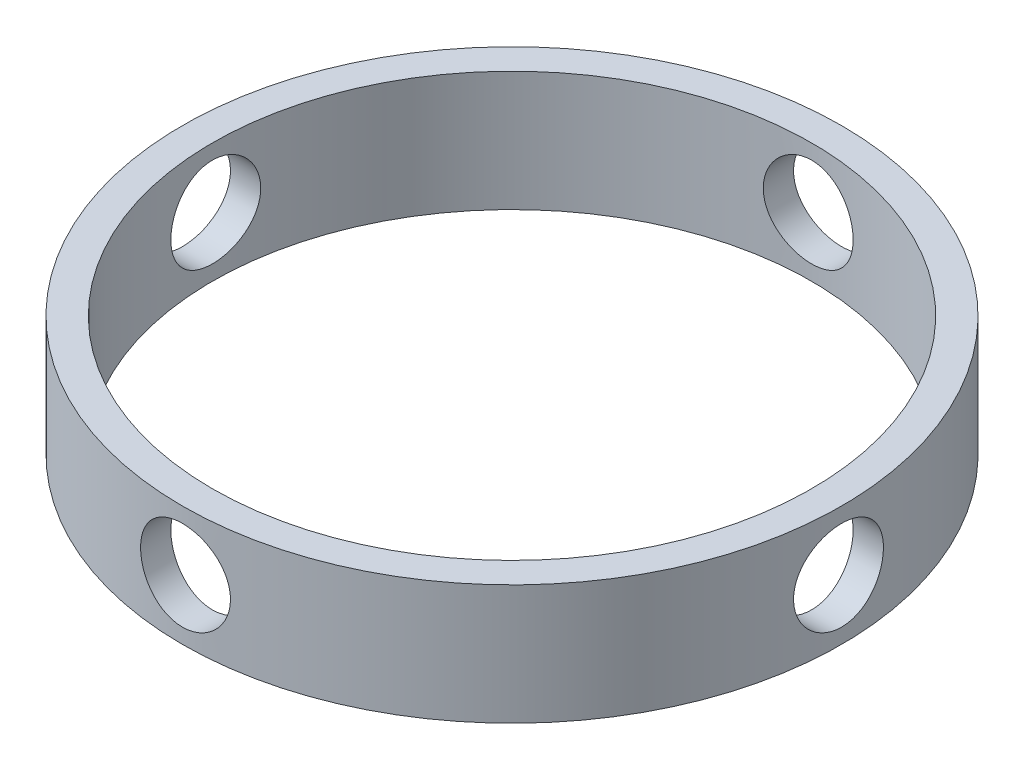
SolidWorks part; units mm, degrees
ref_plane "Front Plane" through (0, 0, 0) normal (0, 0, 1) x (1, 0, 0)
ref_plane "Top Plane" through (0, 0, 0) normal (0, 1, 0) x (1, 0, 0)
ref_plane "Right Plane" through (0, 0, 0) normal (1, 0, 0) x (0, 0, -1)
sketch "Sketch1" plane through (0, 0, 0) normal (0, 1, 0) x (1, 0, 0)
  circle A0 centre (0, 0) radius 55
  circle A1 centre (0, 0) radius 50
  dimension "D1" = 110
  dimension "D2" = 100
extrude "Boss-Extrude1" add sketch "Sketch1" along normal blind 20
sketch "Sketch2" plane through (0, 0, 0) normal (0, 0, 1) x (1, 0, 0)
  line L0 (-55, 20) -> (55, 0) construction
  line L1 (-55, 0) -> (55, 20) construction
  circle A0 centre (0, 10) radius 7.5
  dimension "D1" = 15
extrude "Cut-Extrude1" cut sketch "Sketch2" against normal through all and the other way through all
sketch "Sketch3" plane through (0, 0, 0) normal (1, 0, 0) x (0, 0, -1)
  line L0 (-55, 20) -> (55, 0) construction
  line L1 (55, 20) -> (-55, 0) construction
  circle A0 centre (0, 10) radius 7.5
  dimension "D1" = 15
extrude "Cut-Extrude2" cut sketch "Sketch3" against normal through all and the other way through all
ref_point "Point1"
